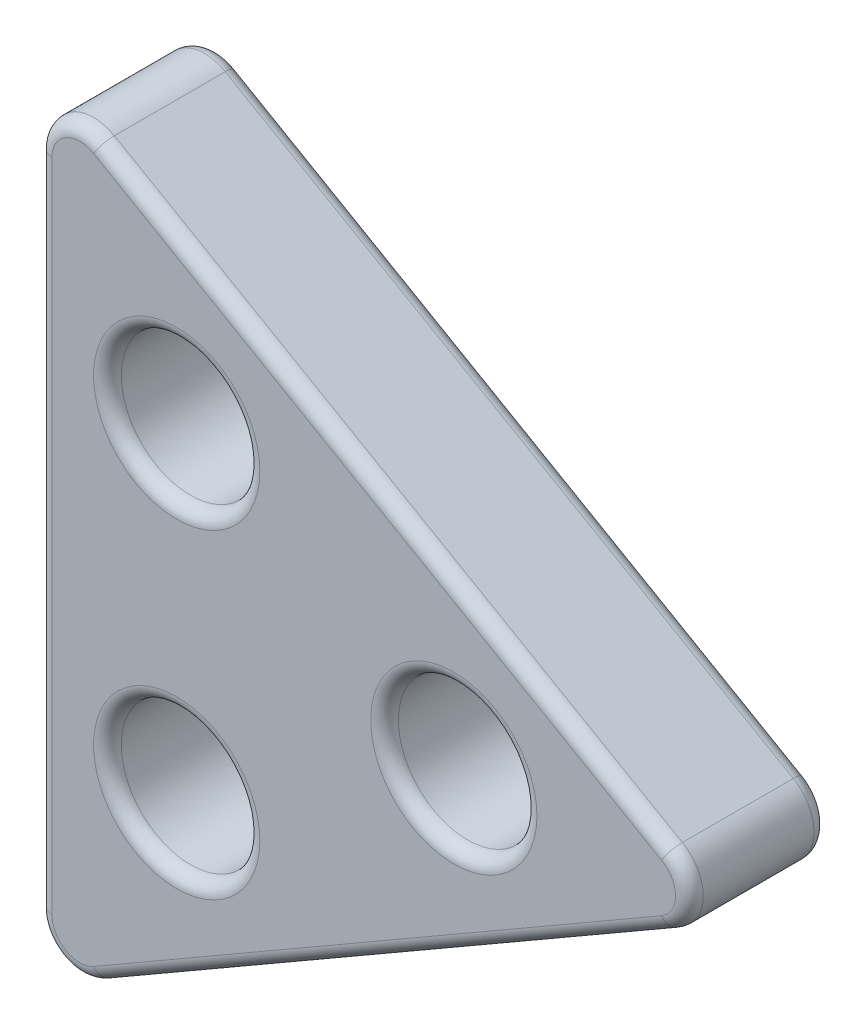
SolidWorks part; units mm, degrees
ref_plane "Front Plane" through (0, 0, 0) normal (0, 0, 1) x (1, 0, 0)
ref_plane "Top Plane" through (0, 0, 0) normal (0, 1, 0) x (1, 0, 0)
ref_plane "Right Plane" through (0, 0, 0) normal (1, 0, 0) x (0, 0, -1)
sketch "Sketch1" plane through (0, 0, 0) normal (0, 0, 1) x (1, 0, 0)
  line L1 (33.3333, 0) -> (-16.6667, 28.8675)
  line L2 (-16.6667, 28.8675) -> (-16.6667, -28.8675)
  line L3 (-16.6667, -28.8675) -> (33.3333, 0)
  circle A0 centre (0, 0) radius 16.6667 construction
  dimension "D1" = 50
extrude "Boss-Extrude1" add sketch "Sketch1" along normal blind 10
sketch "Sketch2" plane through (0, 0, 0) normal (0, 0, -1) x (-1, 0, 0)
  line L1 (-13.3333, 0) -> (6.6667, -11.547) construction
  line L2 (6.6667, -11.547) -> (6.6667, 11.547) construction
  line L3 (6.6667, 11.547) -> (-13.3333, 0) construction
  circle A0 centre (0, 0) radius 6.6667 construction
  circle A1 centre (6.6667, 11.547) radius 5
  circle A2 centre (6.6667, -11.547) radius 5
  circle A3 centre (-13.3333, 0) radius 5
  dimension "D2" = 10
  dimension "D3" = 10
  dimension "D4" = 10
  dimension "D1" = 20
extrude "Cut-Extrude1" cut sketch "Sketch2" against normal blind 10
fillet "Fillet1" radius 3 3 edges at (-16.6667, 28.8675, 5) (33.3333, 0, 5) (-16.6667, -28.8675, 5)
fillet "Fillet2" radius 1 18 edges at (-15.1667, 26.2694, 10) (8.3333, 14.4338, 10) (30.3333, 0, 10) (8.3333, -14.4338, 10) (-15.1667, -26.2694, 10) (30.3333, 0, 0) (8.3333, -14.4338, 0) (-15.1667, -26.2694, 0) (-16.6667, 0, 0) (-15.1667, 26.2694, 0) (-16.6667, 0, 10) (-11.6667, 11.547, 0) (-11.6667, 11.547, 10) (-11.6667, -11.547, 0) (-11.6667, -11.547, 10) (8.3333, 0, 10) (8.3333, 0, 0) (8.3333, 14.4338, 0)
